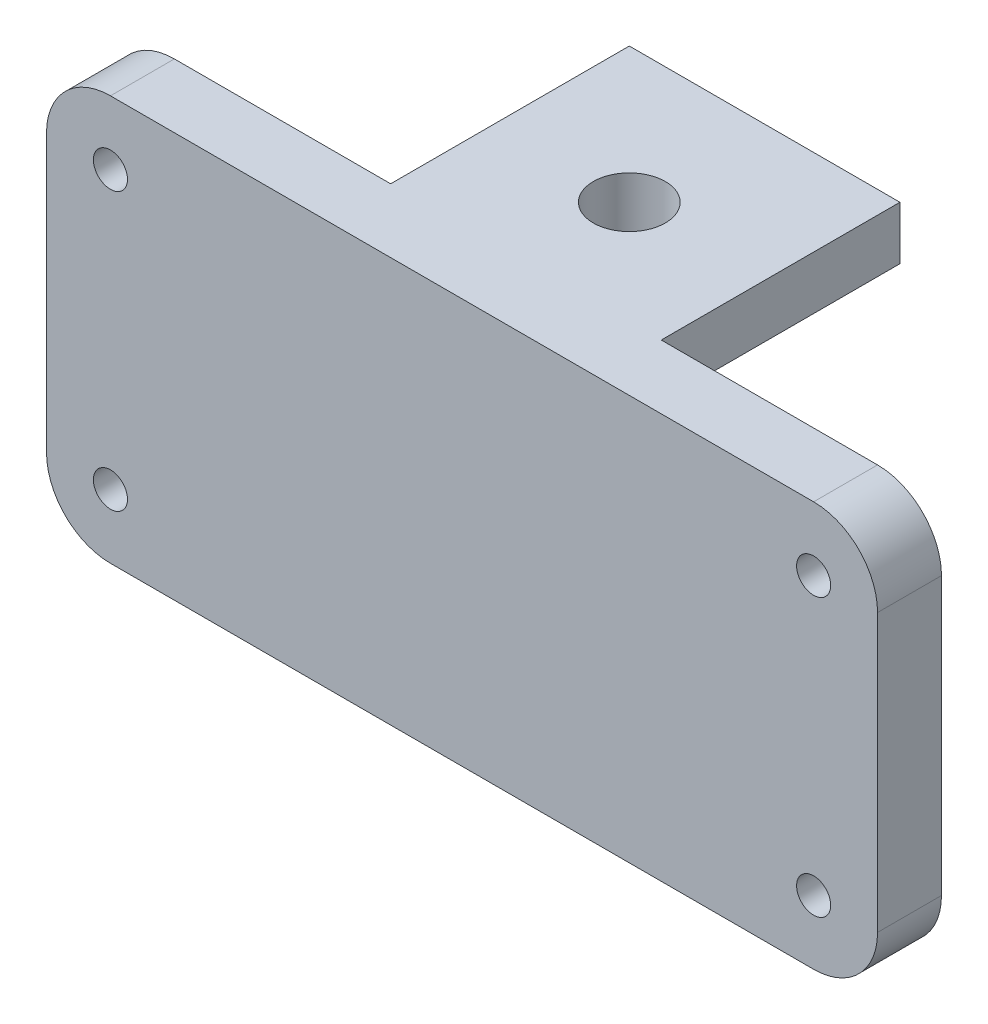
SolidWorks part; units mm, degrees
ref_plane "Front Plane" through (0, 0, 0) normal (0, 0, 1) x (1, 0, 0)
ref_plane "Top Plane" through (0, 0, 0) normal (0, 1, 0) x (1, 0, 0)
ref_plane "Right Plane" through (0, 0, 0) normal (1, 0, 0) x (0, 0, -1)
sketch "Sketch1" plane through (0, 0, 0) normal (0, 1, 0) x (1, 0, 0)
  line L1 (-12.7, 12.7) -> (12.7, 12.7)
  line L2 (-12.7, 12.7) -> (-12.7, -12.7)
  line L3 (-12.7, -12.7) -> (12.7, -12.7)
  line L4 (12.7, 12.7) -> (12.7, -12.7)
  line L5 (-12.7, 12.7) -> (12.7, -12.7) construction
  line L6 (-12.7, -12.7) -> (12.7, 12.7) construction
  point P0 (0, 0)
  dimension "D1" = 25.4
  dimension "D2" = 25.4
extrude "Boss-Extrude1" add sketch "Sketch1" along normal blind 5
hole_wizard "1/4 Clearance Hole1" positions "Sketch2" profile "Sketch3" hole size "1/4" standard "ANSI Inch" end condition through all
sketch "Sketch2" plane through (0, 5, 0) normal (0, 1, 0) x (1, 0, 0)
  point P0 (0, 0)
sketch "Sketch3" plane through (0, 5, 0) normal (1, 0, 0) x (0, 0, 1)
  line L0 (0, 0) -> (0, 5)
  line L1 (0, 5) -> (3.3782, 5)
  line L2 (3.3782, 5) -> (3.3782, 0)
  line L5 (3.3782, 0) -> (0, 0)
  line L11 (0, -6.35) -> (0, 107.95) construction
  dimension "Thru Hole Dia." = 6.7564
  dimension "Thru Hole Depth" = 5
sketch "Sketch4" plane through (0, 0, 12.7) normal (0, 0, 1) x (1, 0, 0)
  line L0 (-39, -33) -> (-39, 5)
  line L1 (-33, -27) -> (33, -27) construction
  line L2 (-33, -27) -> (-33, -1) construction
  line L3 (-33, -1) -> (33, -1) construction
  line L4 (33, -27) -> (33, -1) construction
  line L5 (-33, -27) -> (33, -1) construction
  line L6 (-33, -1) -> (33, -27) construction
  line L7 (-39, 5) -> (39, 5)
  line L8 (39, -33) -> (39, 5)
  line L9 (-39, -33) -> (39, -33)
  line L10 (-12.7, 5) -> (12.7, 5) construction
  circle A0 centre (-33, -1) radius 1.6
  circle A1 centre (33, -1) radius 1.6
  circle A2 centre (33, -27) radius 1.6
  circle A3 centre (-33, -27) radius 1.6
  point P0 (0, -14)
  line M9 (-12.7, 0) -> (12.7, 0)
  line M10 (12.7, 0) -> (12.7, 5)
  line M11 (12.7, 5) -> (-12.7, 5)
  line M12 (-12.7, 5) -> (-12.7, 0)
  dimension "D4" = 3.2
  dimension "D1" = 6
  dimension "D2" = 66
  dimension "D3" = 26
extrude "Boss-Extrude2" add sketch "Sketch4" against normal mid plane 6 contours L0 L9 L8 L7 A3 A2 A1 A0 M10 M9 M12 | M12 M9 M10 M11
fillet "Fillet1" radius 6 4 edges at (39, -33, 12.7) (-39, -33, 12.7) (39, 5, 12.7) (-39, 5, 12.7)
